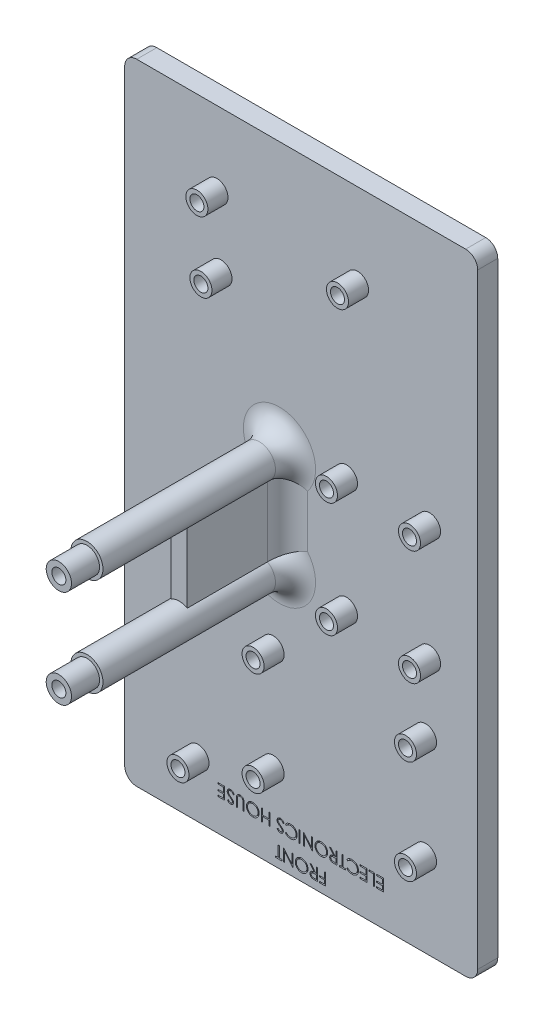
SolidWorks part; units mm, degrees
ref_plane "Front Plane" through (0, 0, 0) normal (1, 0, 0) x (0, 1, 0)
ref_plane "Top Plane" through (0, 0, 0) normal (0, 0, 1) x (0, 1, 0)
ref_plane "Right Plane" through (0, 0, 0) normal (0, 1, 0) x (-1, 0, 0)
sketch "Sketch1" plane through (0, 0, 0) normal (0, 0, 1) x (0, 1, 0)
  line L1 (0, 0) -> (157, 0)
  line L2 (0, 0) -> (0, 88)
  line L3 (0, 88) -> (157, 88)
  line L4 (157, 0) -> (157, 88)
extrude "Boss-Extrude1" add sketch "Sketch1" along normal blind 5
sketch "Sketch2" plane through (0, 0, 5) normal (0, 0, 1) x (1, 0, 0)
  line L0 (-12, 64.24) -> (-6, 64.24) construction
  circle A0 centre (-65, 138.5) radius 2.75
  circle A1 centre (-29.95, 136) radius 2.75
  circle A2 centre (-64, 121.45) radius 2.75
  circle A3 centre (-32.7, 92.84) radius 2.75
  circle A4 centre (-12, 92.84) radius 2.75
  circle A5 centre (-12, 64.24) radius 2.75
  circle A6 centre (-32.7, 64.24) radius 2.75
  circle A7 centre (-51, 46.8) radius 2.75
  circle A8 centre (-13, 46.8) radius 2.75
  circle A9 centre (-13, 21) radius 2.75
  circle A10 centre (-51, 21) radius 2.75
  circle A11 centre (-69.72, 13.98) radius 2.75
  circle A13 centre (-66.72, 66.98) radius 2.75
extrude "Boss-Extrude2" add sketch "Sketch2" along normal blind 5
sketch "Sketch3" plane through (0, 0, 5) normal (0, 0, 1) x (1, 0, 0)
  circle A0 centre (-69.72, 13.98) radius 1.75
  circle A1 centre (-51, 21) radius 1.75
  circle A2 centre (-13, 21) radius 1.75
  circle A3 centre (-13, 46.8) radius 1.75
  circle A4 centre (-51, 46.8) radius 1.75
  circle A6 centre (-32.7, 64.24) radius 1.75
  circle A7 centre (-12, 64.24) radius 1.75
  circle A8 centre (-32.7, 92.84) radius 1.75
  circle A9 centre (-12, 92.84) radius 1.75
  circle A10 centre (-64, 121.45) radius 1.75
  circle A11 centre (-65, 138.5) radius 1.75
  circle A12 centre (-29.95, 136) radius 1.75
  circle A13 centre (-66.72, 66.98) radius 1.75
extrude "Cut-Extrude1" cut sketch "Sketch3" along normal blind 5
sketch "Sketch4" plane through (0, 0, 5) normal (0, 0, 1) x (1, 0, 0)
  line L1 (-49.4105, 78.5049) -> (-49.4105, 66.3049) construction
  line L2 (-49.4105, 78.5049) -> (-49.4105, 90.7049) construction
  circle A0 centre (-49.4105, 66.3049) radius 4
  circle A1 centre (-49.4105, 90.7049) radius 4
extrude "Boss-Extrude3" add sketch "Sketch4" along normal blind 55
sketch "Sketch5" plane through (0, 0, 60) normal (0, 0, 1) x (1, 0, 0)
  circle A1 centre (-49.4105, 90.7049) radius 4
  circle A2 centre (-49.4105, 66.3049) radius 4
extrude "Cut-Extrude2" cut sketch "Sketch5" against normal blind 7
sketch "Sketch6" plane through (0, 0, 53) normal (0, 0, 1) x (1, 0, 0)
  circle A0 centre (-49.4105, 90.7049) radius 3.15
  circle A1 centre (-49.4105, 66.3049) radius 3.15
extrude "Boss-Extrude4" add sketch "Sketch6" along normal blind 7
sketch "Sketch7" plane through (0, 0, 60) normal (0, 0, 1) x (1, 0, 0)
  circle A0 centre (-49.4105, 66.3049) radius 1.75
  circle A1 centre (-49.4105, 90.7049) radius 1.75
extrude "Cut-Extrude3" cut sketch "Sketch7" against normal blind 5
sketch "Sketch8" plane through (0, 0, 5) normal (0, 0, 1) x (1, 0, 0)
  line L6 (-49.4105, 90.7049) -> (-47.4105, 90.7049)
  line L7 (-49.4105, 90.7049) -> (-51.4105, 90.7049)
  line L8 (-49.4105, 66.3049) -> (-51.4105, 66.3049)
  line L9 (-49.4105, 66.3049) -> (-47.4105, 66.3049)
  line L10 (-51.4105, 90.7049) -> (-51.4105, 66.3049)
  line L11 (-47.4105, 90.7049) -> (-47.4105, 66.3049)
extrude "Boss-Extrude5" add sketch "Sketch8" along normal blind 25
fillet "Fillet2" radius 5 4 edges at (-49.4105, 62.3049, 5) (-49.4105, 94.7049, 5) (-47.4105, 78.5049, 5) (-51.4105, 78.5049, 5)
fillet "Fillet3" radius 3 4 edges at (0, 0, 2.5) (-88, 0, 2.5) (-88, 157, 2.5) (0, 157, 2.5)
sketch "Sketch12" plane through (0, 0, 5) normal (0, 0, 1) x (1, 0, 0)
  line L0 (-44, 0) -> (-44, 5) construction
  line L1 (-85, 0) -> (-3, 0) construction
  line L2 (-14, 5) -> (-74, 5) construction
  text T0 "FRONT\r\nELECTRONICS HOUSE" font "Century Gothic" height 3
  point P7 (-44, 5)
extrude "Cut-Extrude7" cut sketch "Sketch12" against normal blind 1
